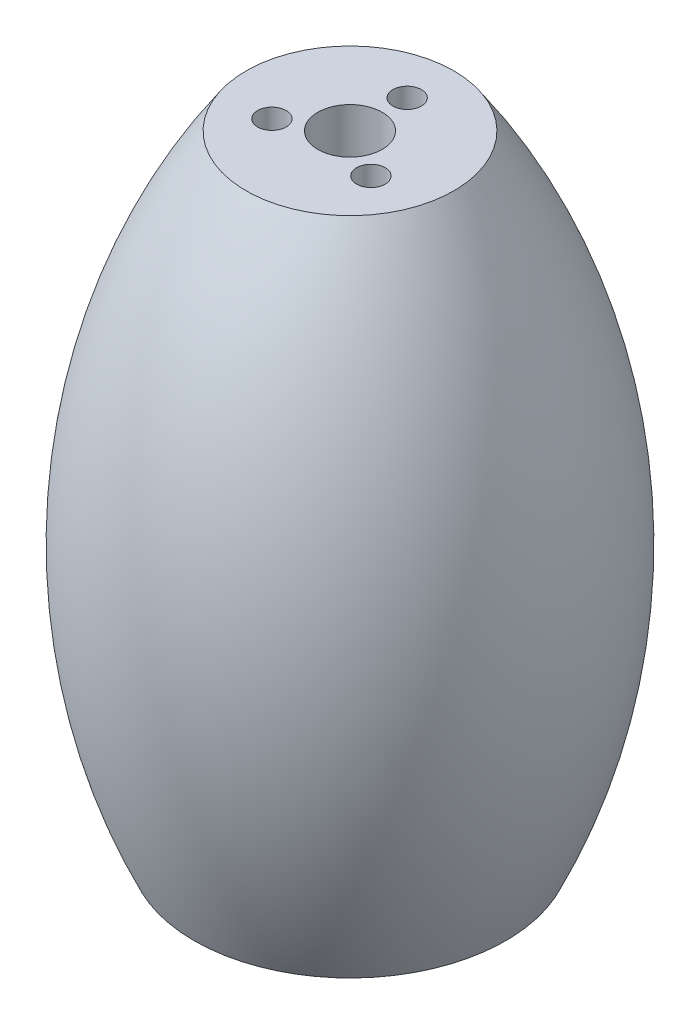
SolidWorks part; units mm, degrees
ref_plane "正面" through (0, 0, 0) normal (0, 0, 1) x (1, 0, 0)
ref_plane "平面" through (0, 0, 0) normal (0, 1, 0) x (1, 0, 0)
ref_plane "右側面" through (0, 0, 0) normal (1, 0, 0) x (0, 0, -1)
sketch "ｽｹｯﾁ1" plane through (0, 0, 0) normal (0, 0, 1) x (1, 0, 0)
  line L0 (-30, 0) -> (0, 0)
  line L1 (0, 0) -> (0, 120)
  line L2 (0, 120) -> (-20, 120)
  arc A0 (-30, 0) -> (-20, 120) centre (80, 51.25) cw
  point P7 (0, 0)
  point P8 (-27.9524, 100.1212)
  dimension "D1" = 120
  dimension "D2" = 30
  dimension "D3" = 20
  dimension "D4" = 80
revolve "回転1" add sketch "ｽｹｯﾁ1" angle 360 about L1
sketch "ｽｹｯﾁ2" plane through (0, 120, 0) normal (0, 1, 0) x (1, 0, 0)
  line L0 (0, 0) -> (0, 11) construction
  line L1 (-9.5263, -5.5) -> (0, 0) construction
  line L2 (0, 0) -> (9.5263, -5.5) construction
  circle A0 centre (0, 11) radius 2.75
  circle A1 centre (9.5263, -5.5) radius 2.75
  circle A2 centre (-9.5263, -5.5) radius 2.75
  dimension "D1" = 5.5
  dimension "D2" = 11
  dimension "D3" = 3
extrude "ｶｯﾄ - 押し出し1" cut sketch "ｽｹｯﾁ2" against normal blind 5
ref_plane "平面1" through (0, 60, 0) normal (0, 1, 0) x (1, 0, 0)
mirror "ﾐﾗｰ1" about plane through (0, 60, 0) normal (0, 1, 0) of "ｶｯﾄ - 押し出し1"
sketch "ｽｹｯﾁ3" plane through (0, 120, 0) normal (0, 1, 0) x (1, 0, 0)
  circle A0 centre (0, 0) radius 6.2
  dimension "D1" = 12.4
extrude "ｶｯﾄ - 押し出し2" cut sketch "ｽｹｯﾁ3" against normal through all
